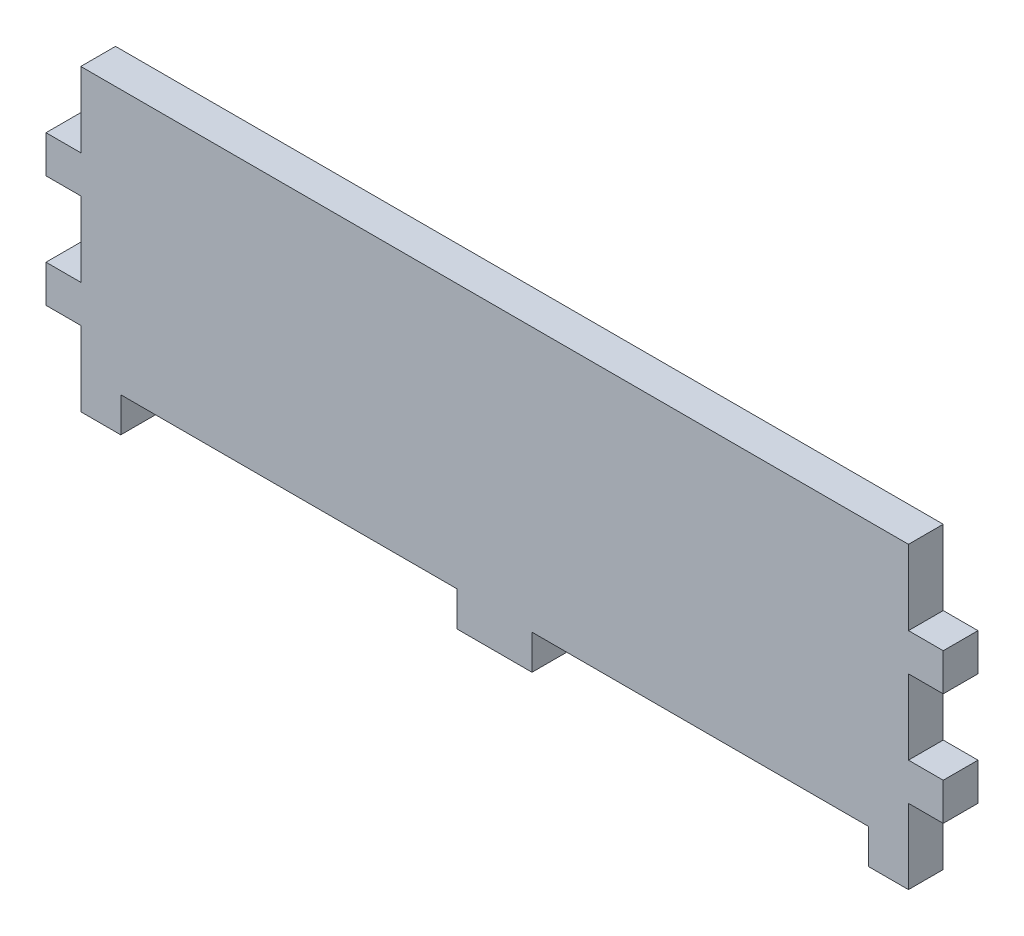
SolidWorks part; units mm, degrees
material "Oak"
ref_plane "Front Plane" through (0, 0, 0) normal (0, 0, 1) x (1, 0, 0)
ref_plane "Top Plane" through (0, 0, 0) normal (0, 1, 0) x (1, 0, 0)
ref_plane "Right Plane" through (0, 0, 0) normal (1, 0, 0) x (0, 0, -1)
sketch "Base_Sketch" plane through (0, 0, 0) normal (0, 0, 1) x (1, 0, 0)
  line L0 (-699.3487, -38.9178) -> (-370.9287, -38.9178) construction
  line L1 (-687.5387, -50.7278) -> (-382.7387, -50.7278)
  line L2 (-687.5387, -50.7278) -> (-687.5387, -140.5178)
  line L3 (-687.5387, -140.5178) -> (-382.7387, -140.5178)
  line L4 (-382.7387, -50.7278) -> (-382.7387, -140.5178)
  line L5 (-687.5387, -50.7278) -> (-382.7387, -140.5178) construction
  line L6 (-687.5387, -140.5178) -> (-382.7387, -50.7278) construction
  line L7 (-370.9287, -38.9178) -> (-370.9287, -152.3278) construction
  line L8 (-699.3487, -152.3278) -> (-370.9287, -152.3278) construction
  line L9 (-699.3487, -38.9178) -> (-699.3487, -152.3278) construction
  line L12 (-382.7387, -50.7278) -> (-382.7387, -152.3278) construction
  line L13 (-687.5387, -50.7278) -> (-382.7387, -50.7278) construction
  dimension "D1" = 11.81
extrude "Boss-Extrude1" add sketch "Base_Sketch" along normal blind 11.81
sketch "Joint_X" plane through (0, 0, 11.81) normal (0, 0, 1) x (1, 0, 0)
  line L1 (-687.5387, -152.3278) -> (-662.1387, -152.3278)
  line L2 (-687.5387, -152.3278) -> (-687.5387, -140.5178)
  line L3 (-687.5387, -140.5178) -> (-662.1387, -140.5178)
  line L4 (-662.1387, -152.3278) -> (-662.1387, -140.5178)
  point P5 (-662.1387, -146.4228)
  dimension "D1" = 11.81
  dimension "D2" = 25.4
sketch "Joint_Y" plane through (0, 0, 11.81) normal (0, 0, 1) x (1, 0, 0)
  line L1 (-687.5387, -152.3278) -> (-675.7287, -152.3278)
  line L2 (-687.5387, -152.3278) -> (-687.5387, -126.9278)
  line L3 (-687.5387, -126.9278) -> (-675.7287, -126.9278)
  line L4 (-675.7287, -152.3278) -> (-675.7287, -126.9278)
  dimension "D1" = 11.81
  dimension "D2" = 25.4
extrude "Boss-Extrude2" add sketch "Joint_X" against normal blind 11.81
extrude "Cut-Extrude1" cut sketch "Joint_Y" against normal through all
pattern_linear "LPattern1" count 3 spacing 139.7 along (1, 0, 0) of "Boss-Extrude2"
ref_plane "Plane1" through (-535.1387, 0, 0) normal (-1, 0, 0) x (0, 0, 1)
pattern_linear "LPattern2" count 3 spacing 38.1 along (0, 1, 0) of "Cut-Extrude1"
mirror "Mirror1" about plane through (-535.1387, 0, 0) normal (-1, 0, 0) of "LPattern2", "Cut-Extrude1"
equation "\"Material_Thickness\"= \"Material_Thickness@Petrov.Assembly\""
equation "\"D1@Boss-Extrude1\"=\"Material_Thickness\""
equation "\"D1@Joint_X\" = \"Material_Thickness\""
equation "\"D1@Joint_Y\" = \"Material_Thickness\""
equation "\"D1@Boss-Extrude2\"=\"Material_Thickness\""
equation "\"Num_Joints\"= \"Cover_Num_Joints@Petrov.Assembly\""
equation "\"D1@LPattern1\"=\"Num_Joints\""
equation "\"D1@Base_Sketch\"=\"Material_Thickness\""
equation "\"D1@LPattern2\"=\"Num_Joints\""
equation "\"Joint_Size\"= \"Cover_Joint_Size@Petrov.Assembly\""
equation "\"D2@Joint_Y\"=\"Joint_Size\""
equation "\"D2@Joint_X\"=\"Joint_Size\""
